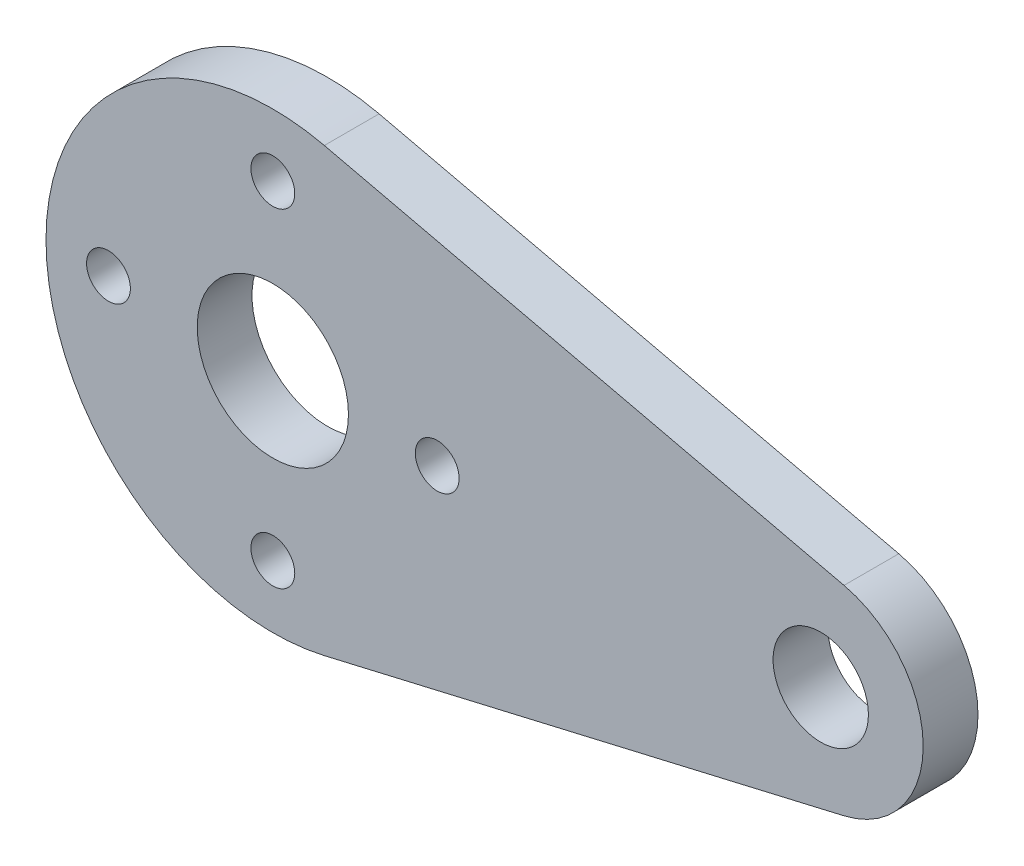
SolidWorks part; units mm, degrees
ref_plane "Front Plane" through (0, 0, 0) normal (0, 0, 1) x (1, 0, 0)
ref_plane "Top Plane" through (0, 0, 0) normal (0, 1, 0) x (1, 0, 0)
ref_plane "Right Plane" through (0, 0, 0) normal (1, 0, 0) x (0, 0, -1)
sketch "Sketch1" plane through (0, 0, 0) normal (0, 0, 1) x (1, 0, 0)
  line L0 (4.6989, 20.1596) -> (52.1225, 9.1059)
  line L1 (0, 0) -> (50, 0) construction
  line L2 (4.6989, -20.1596) -> (52.1225, -9.1059)
  circle A0 centre (0, 0) radius 6.9
  circle A1 centre (50, 0) radius 4.35
  arc A2 (4.6989, 20.1596) -> (4.6989, -20.1596) centre (0, 0) ccw
  arc A3 (52.1225, -9.1059) -> (52.1225, 9.1059) centre (50, 0) ccw
  circle A4 centre (15, 0) radius 2
  circle A5 centre (0, -15) radius 2
  circle A6 centre (-15, 0) radius 2
  circle A7 centre (0, 15) radius 2
  point P20 (0, 0)
  dimension "D1" = 13.8
  dimension "D2" = 8.7
  dimension "D4" = 13.8
  dimension "D5" = 5
  dimension "D6" = 4
  dimension "D3" = 50
  dimension "D7" = 15
  dimension "D8" = 4
extrude "Boss-Extrude1" add sketch "Sketch1" along normal blind 5
sketch "Sketch2" plane through (0, 0, 5) normal (0, 0, 1) x (1, 0, 0)
  line L0 (-15, 0) -> (15, 0) construction
  line L1 (0, 15) -> (0, -15) construction
